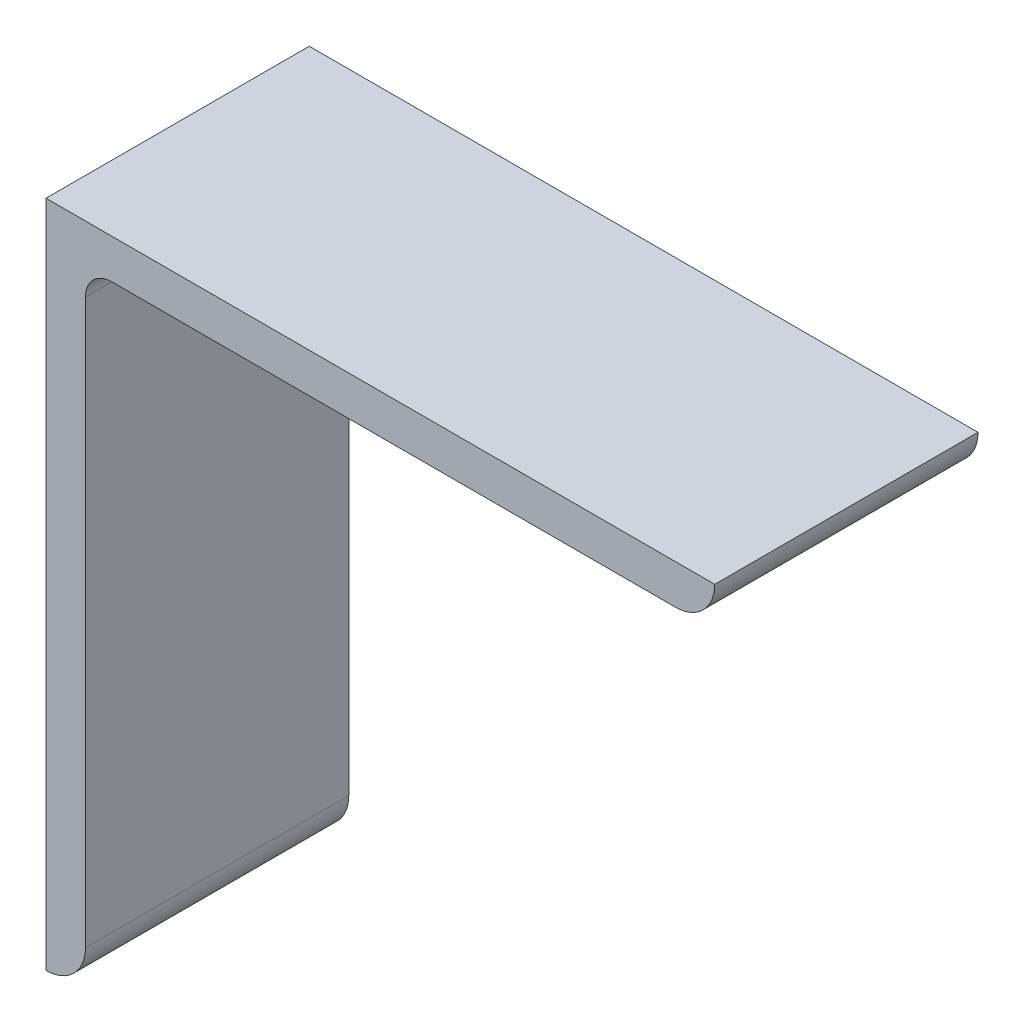
SolidWorks part; units mm, degrees
ref_plane "Alzado" through (0, 0, 0) normal (0, 0, 1) x (1, 0, 0)
ref_plane "Planta" through (0, 0, 0) normal (0, 1, 0) x (1, 0, 0)
ref_plane "Vista lateral" through (0, 0, 0) normal (1, 0, 0) x (0, 0, -1)
sketch "Croquis1" plane through (0, 0, 0) normal (0, 0, 1) x (1, 0, 0)
  line L0 (22.2085, 22.2085) -> (-20.5915, 22.2085)
  line L1 (-22.5915, -22.5915) -> (-22.5915, 22.2085) construction
  line L2 (22.2085, 22.2085) -> (-22.5915, 22.2085) construction
  line L3 (25.2085, 25.2085) -> (-25.5915, 25.2085)
  line L4 (-25.5915, -25.5915) -> (-25.5915, 25.2085)
  line L6 (25.2085, 25.2085) -> (-25.5915, -25.5915) construction
  line L7 (-22.5915, -22.5915) -> (-22.5915, 20.2085)
  line L10 (25.2085, -25.5915) -> (25.2085, 25.2085) construction
  line L11 (22.2085, -22.5915) -> (22.2085, 22.2085) construction
  line L12 (-0.1915, -0.1915) -> (-25.5915, 25.2085) construction
  line L13 (22.2085, -22.5915) -> (-22.5915, -22.5915) construction
  line L14 (25.2085, -25.5915) -> (-25.5915, -25.5915) construction
  arc A0 (25.2085, 25.2085) -> (22.2085, 22.2085) centre (22.2085, 25.2085) cw
  arc A1 (-22.5915, -22.5915) -> (-25.5915, -25.5915) centre (-25.5915, -22.5915) cw
  arc A2 (-22.5915, 20.2085) -> (-20.5915, 22.2085) centre (-20.5915, 20.2085) cw
  point P0 (0, 0)
  dimension "D4" = 2
  dimension "D1" = 50.8
  dimension "D2" = 50.8
  dimension "D3" = 3
extrude "Saliente-Extruir1" add sketch "Croquis1" along normal blind 20
